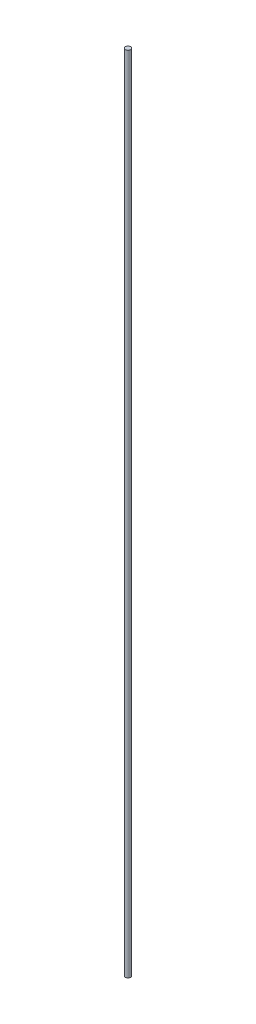
SolidWorks part; units mm, degrees
ref_plane "Front" through (0, 0, 0) normal (0, 0, 1) x (1, 0, 0)
ref_plane "Top" through (0, 0, 0) normal (0, 1, 0) x (1, 0, 0)
ref_plane "Right" through (0, 0, 0) normal (1, 0, 0) x (0, 0, -1)
sketch "Sketch1" plane through (0, 0, 0) normal (0, 1, 0) x (1, 0, 0)
  circle A0 centre (0, 0) radius 3.9687
  dimension "D1" = 7.9375
extrude "Boss-Extrude1" add sketch "Sketch1" along normal blind 1219.2
